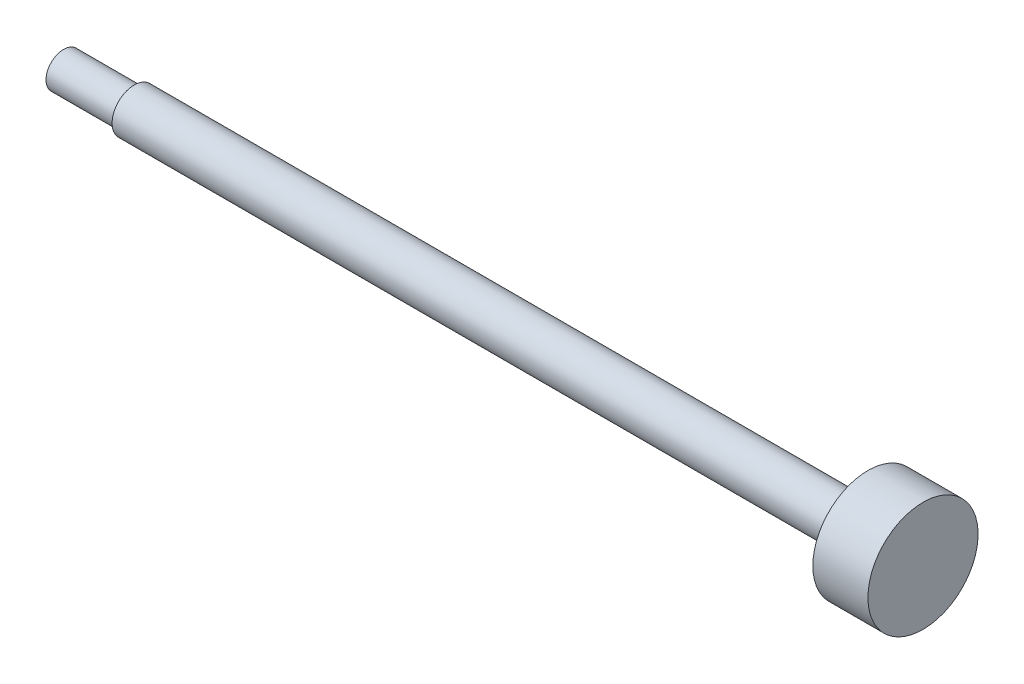
SolidWorks part; units mm, degrees
ref_plane "Front Plane" through (0, 0, 0) normal (0, 0, 1) x (1, 0, 0)
ref_plane "Top Plane" through (0, 0, 0) normal (0, 1, 0) x (1, 0, 0)
ref_plane "Right Plane" through (0, 0, 0) normal (1, 0, 0) x (0, 0, -1)
sketch "Esquisse1" plane through (0, 0, 0) normal (0, 0, 1) x (1, 0, 0)
  line L0 (0, 0) -> (326.0092, 0) construction
  line L1 (0, 0) -> (0, 8)
  line L2 (0, 8) -> (32, 8)
  line L3 (32, 8) -> (32, 10)
  line L4 (32, 10) -> (365, 10)
  line L5 (365, 10) -> (365, 25)
  line L6 (390, 0) -> (0, 0)
  line L7 (390, 25) -> (390, 0)
  line L13 (365, 25) -> (390, 25)
  dimension "D1" = 390
  dimension "D2" = 32
  dimension "D3" = 50
  dimension "D4" = 8
  dimension "D5" = 10
  dimension "D9" = 25
revolve "Révolution1" add sketch "Esquisse1" angle 360 about L0
